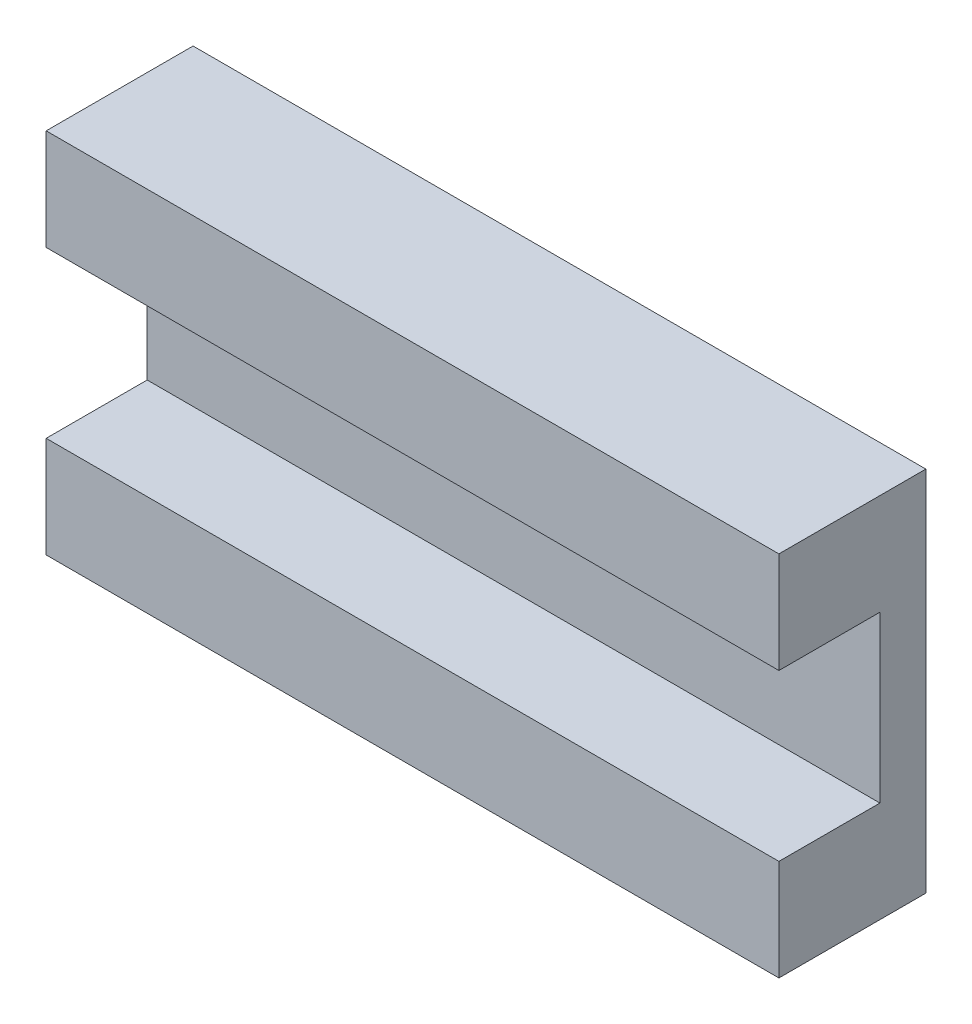
SolidWorks part; units mm, degrees
ref_plane "前视基准面" through (0, 0, 0) normal (0, 0, 1) x (1, 0, 0)
ref_plane "上视基准面" through (0, 0, 0) normal (0, 1, 0) x (1, 0, 0)
ref_plane "右视基准面" through (0, 0, 0) normal (1, 0, 0) x (0, 0, -1)
sketch "草图1" plane through (0, 0, 0) normal (0, 0, 1) x (1, 0, 0)
  line L1 (0, 0) -> (-39.9, 0)
  line L2 (0, 0) -> (0, 20)
  line L3 (0, 20) -> (-39.9, 20)
  line L4 (-39.9, 0) -> (-39.9, 20)
  dimension "D1" = 20
  dimension "D2" = 39.9
extrude "凸台-拉伸1" add sketch "草图1" along normal blind 8
sketch "草图2" plane through (0, 0, 0) normal (0, 0, -1) x (-1, 0, 0)
  line L0 (19.95, 20) -> (19.95, 17.5) construction
  line L1 (0, 20) -> (39.9, 20) construction
  line L2 (19.95, 17.5) -> (11.95, 17.5) construction
  line L3 (19.95, 17.5) -> (27.95, 17.5) construction
  line L4 (0, 10) -> (3.2896, 10) construction
  line L5 (0, 0) -> (0, 20) construction
  circle A0 centre (11.95, 17.5) radius 1.5
  circle A1 centre (27.95, 17.5) radius 1.5
  circle A2 centre (27.95, 2.5) radius 1.5
  circle A3 centre (11.95, 2.5) radius 1.5
  dimension "D4" = 3
  dimension "D5" = 3
  dimension "D1" = 2.5
  dimension "D2" = 8
  dimension "D3" = 8
extrude "切除-拉伸1" cut sketch "草图2" against normal blind 3
sketch "草图3" plane through (0, 0, 0) normal (1, 0, 0) x (0, 0, -1)
  line L0 (-8, 0) -> (-8, 20) construction
  line L1 (-8, 14.5) -> (-2.5, 14.5)
  line L2 (-8, 14.5) -> (-8, 5.5)
  line L3 (-8, 5.5) -> (-2.5, 5.5)
  line L4 (-2.5, 14.5) -> (-2.5, 5.5)
  line L5 (-8, 20) -> (0, 20) construction
  dimension "D1" = 9
  dimension "D2" = 5.5
  dimension "D3" = 5.5
extrude "切除-拉伸2" cut sketch "草图3" against normal through all
